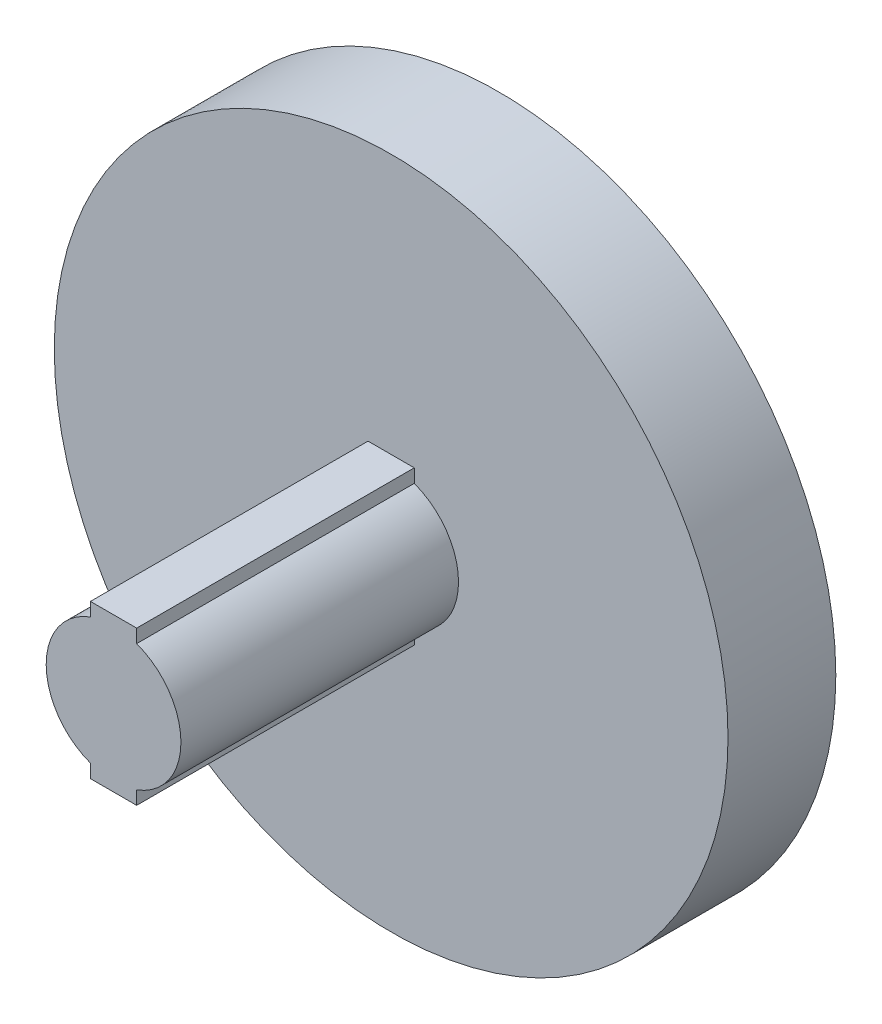
SolidWorks part; units mm, degrees
ref_plane "Front Plane" through (0, 0, 0) normal (1, 0, 0) x (0, 1, 0)
ref_plane "Top Plane" through (0, 0, 0) normal (0, 0, 1) x (0, 1, 0)
ref_plane "Right Plane" through (0, 0, 0) normal (0, 1, 0) x (-1, 0, 0)
sketch "Sketch1" plane through (0, 0, 0) normal (0, 0, 1) x (0, 1, 0)
  circle A0 centre (0, 0) radius 25
  dimension "D1" = 50
extrude "Boss-Extrude1" add sketch "Sketch1" along normal blind 8
sketch "Sketch2" plane through (0, 0, 8) normal (0, 0, 1) x (1, 0, 0)
  line L0 (-1.7151, 4.6966) -> (-1.7151, 5.6966)
  line L1 (-1.7151, -5.6966) -> (1.7151, -5.6966)
  line L2 (-1.7151, -5.6966) -> (-1.7151, -4.6966)
  line L3 (-1.7151, 5.6966) -> (1.7151, 5.6966)
  line L4 (1.7151, -5.6966) -> (1.7151, -4.6966)
  line L7 (1.7151, 4.6966) -> (1.7151, 5.6966)
  arc A0 (1.7151, -4.6966) -> (1.7151, 4.6966) centre (0, 0) ccw
  arc A1 (-1.7151, 4.6966) -> (-1.7151, -4.6966) centre (0, 0) ccw
  dimension "D1" = 10
  dimension "D2" = 1
  dimension "D3" = 1
extrude "Boss-Extrude2" add sketch "Sketch2" along normal blind 20.6 contours A0 L7 L3 L0 A1 L2 L1 L4
